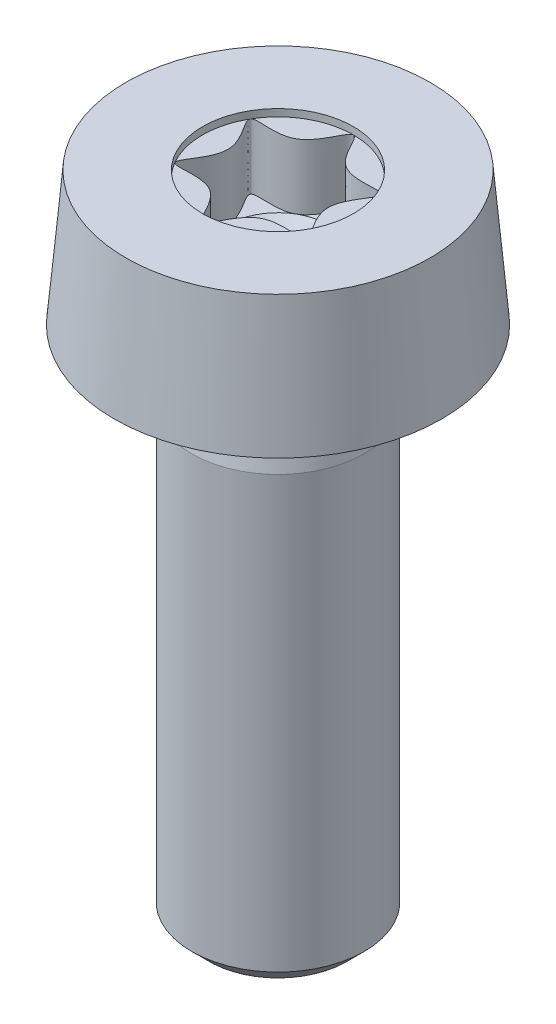
SolidWorks part; units mm, degrees
material "AISI 304"
ref_plane "Front" through (0, 0, 0) normal (0, 0, 1) x (1, 0, 0)
ref_plane "Top" through (0, 0, 0) normal (0, 1, 0) x (1, 0, 0)
ref_plane "Right" through (0, 0, 0) normal (1, 0, 0) x (0, 0, -1)
other "Configuration Table"
sketch "Sketch1" plane through (0, 0, 0) normal (0, 0, 1) x (1, 0, 0)
  line L0 (0, 0) -> (0, 5.1006) construction
  line L1 (0, 7.55) -> (1.7644, 7.55)
  line L2 (1.7644, 7.55) -> (1.9, 6)
  line L3 (1.9, 6) -> (1, 6)
  line L4 (1, 0) -> (1, 5.2)
  line L5 (1, 0) -> (0, 0)
  line L6 (0, 0) -> (0, 7.55)
  line L7 (1.9, 6) -> (1.9, 5.6) construction
  line L8 (1, 5.2) -> (0.84, 6)
  line L9 (0.84, 6) -> (1, 6)
  line L10 (1.9, 5.6) -> (1.9, 0.1) construction
  dimension "length" = 6
  dimension "head_ht" = 1.55
  dimension "head_dia" = 3.8
  dimension "dia" = 2
  dimension "D1" = 5
  dimension "pitch" = 0.4
  dimension "thread_gap" = 0.8
  dimension "D2" = 0.16
  dimension "thread_length" = 5.5
revolve "Body-Revolve" add sketch "Sketch1" angle 360 about L0
cosmetic thread "ThreadCosmetic" parameters "D1"=5.5, "D2"=1.567
fillet "Fillet1" radius 0.1 1 edges at (0, 6, -0.84)
sketch "Sketch2" plane through (0, 7.55, 0) normal (0, 1, 0) x (-1, 0, 0)
  line L0 (0, -0.9625) -> (0, 0)
  line L1 (0, 0) -> (-0.4375, -0.7578)
  circle A0 centre (0, 0) radius 0.875
  circle A1 centre (0, 0) radius 0.5833
  spline S0 degree 3 poles (0.1887, -0.3269) (0, -1.1491) (-0.1887, -0.3269) (-0.9951, -0.5745) (-0.3774, 0) (-0.9951, 0.5745) (-0.1887, 0.3269) (0, 1.1491) (0.1887, 0.3269) (0.9951, 0.5745) (0.3774, 0) (0.9951, -0.5745) (0.1887, -0.3269) (0, -1.1491) (-0.1887, -0.3269) knots -0.25 -0.166667 -0.083333 0 0.083333 0.166667 0.25 0.333333 0.416667 0.5 0.583333 0.666667 0.75 0.833333 0.916667 1 1.083333 1.166667 1.25 only from (0, -0.875) to (0, -0.875)
  point P5 (0, -0.875)
  point P7 (-0.2917, -0.5052)
  point P10 (-0.7578, -0.4375)
  point P11 (-0.7578, 0.4375)
  point P12 (0, 0.875)
  point P13 (0.7578, 0.4375)
  point P14 (0.7578, -0.4375)
  point P15 (-0.5833, 0)
  point P16 (-0.2917, 0.5052)
  point P17 (0.2917, 0.5052)
  point P18 (0.5833, 0)
  point P19 (0.2917, -0.5052)
  dimension "socket_dia" = 1.75
  dimension "D1" = 1.1667
  dimension "D2" = 0.9625
  dimension "D3" = 30
extrude "Socket-Cut-Extrude1" cut sketch "Sketch2" against normal blind 0.84 contours S0
sketch "Sketch3" plane through (0, 7.55, 0) normal (0, 1, 0) x (-1, 0, 0)
  circle A0 centre (0, 0) radius 0.875
  dimension "D1" = 1.75
extrude "Socket-Cut-Extrude2" cut sketch "Sketch3" against normal blind 0.084
sketch "Sketch4" plane through (0, 0, 0) normal (0, 0, 1) x (1, 0, 0)
  line L0 (0, 6.71) -> (0.5833, 6.71)
  line L1 (0.761, 6.71) -> (-0.761, 6.71) construction
  line L2 (0.5833, 6.71) -> (0, 6.155)
  line L3 (0, 0) -> (0, 5.1006) construction
  line L4 (0, 6.155) -> (0, 6.71)
  line L5 (0.875, 7.55) -> (-0.875, 7.55) construction
  dimension "D1" = 1.395
  dimension "D2" = 0.5833
revolve "Drill-Cut-Revolve" cut sketch "Sketch4" angle 360 about axis through (0, 0, 0) along (0, 1, 0)
sketch "Sketch5" plane through (0, 0, 0) normal (0, 0, 1) x (1, 0, 0)
  line L0 (1, 0) -> (0.7835, 0.125)
  line L1 (0.7835, 0.125) -> (1, 0.25)
  line L2 (1, 0) -> (1, 5.2) construction
  line L3 (1, 0.25) -> (1, 0)
  line L4 (0, 0) -> (0, 5.1006) construction
  dimension "D1" = 0.7835
revolve "ThreadSchematic" [suppressed] cut sketch "Sketch5" angle 360 about axis through (0, 0, 0) along (0, 1, 0)
pattern_linear "ThdSchPat" [suppressed] count 14 spacing 0.4 along (0, 1, 0)
chamfer "Chaflán1" distance 0.2 angle 45 1 edges at (0, 0, -1)
equation "\"D2@Sketch1\" = 0.2*\"thread_gap@Sketch1\""
equation "\"D1@Sketch2\" = \"socket_dia@Sketch2\" / 1.5"
equation "\"D2@Sketch2\" = \"socket_dia@Sketch2\" / 2 * 1.1"
equation "\"D1@Sketch3\" =\"socket_dia@Sketch2\""
equation "\"D1@Socket-Cut-Extrude2\" = .1 * \"socket_dep@Socket-Cut-Extrude1\""
equation "\"D1@Sketch4\" = 0.9*\"head_ht@Sketch1\""
equation "\"D2@Sketch4\" = \"D1@Sketch2\" / 2"
equation "\"D1@ThreadCosmetic\" = \"thread_length@Sketch1\""
equation "\"D2@ThreadCosmetic\" = \"dia@Sketch1\" - 1.0825 * \"pitch@Sketch1\""
equation "\"D1@Sketch5\" = \"D2@ThreadCosmetic\" / 2"
equation "\"D3@ThdSchPat\" = \"pitch@Sketch1\""
equation "\"D1@ThdSchPat\" = \"thread_length@Sketch1\" / \"pitch@Sketch1\""
